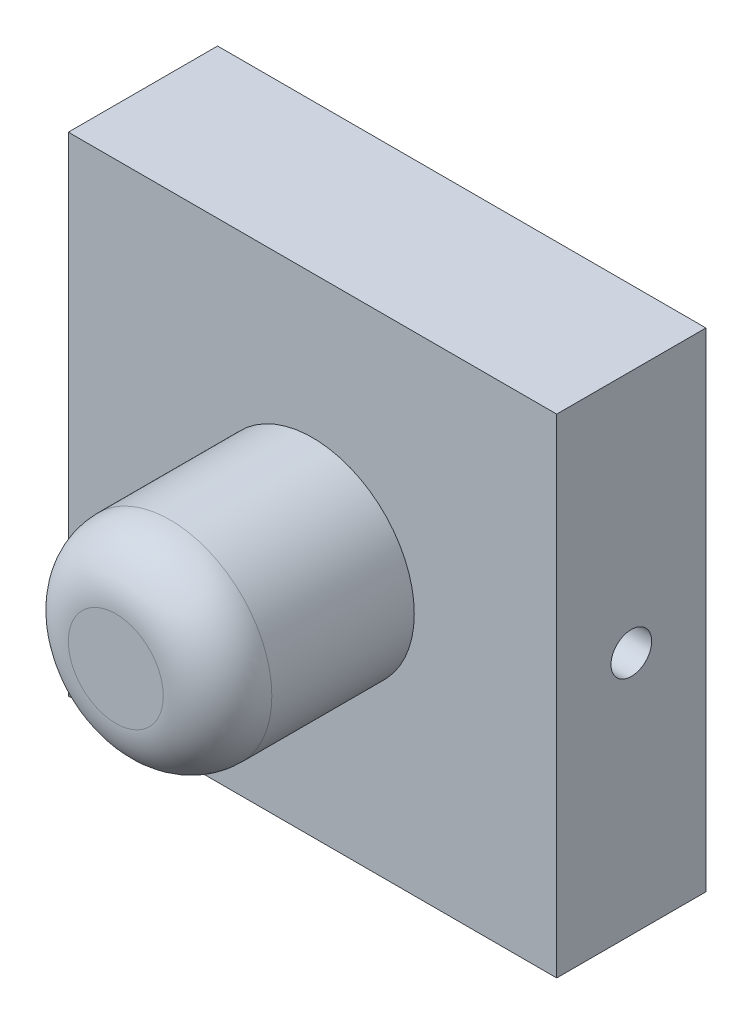
SolidWorks part; units mm, degrees
ref_plane "前视基准面" through (0, 0, 0) normal (0, 0, 1) x (1, 0, 0)
ref_plane "上视基准面" through (0, 0, 0) normal (0, 1, 0) x (1, 0, 0)
ref_plane "右视基准面" through (0, 0, 0) normal (1, 0, 0) x (0, 0, -1)
sketch "草图1" plane through (0, 0, 0) normal (1, 0, 0) x (0, 0, -1)
  line L1 (-5.5, -18) -> (5.5, -18)
  line L2 (-5.5, -18) -> (-5.5, 18)
  line L3 (-5.5, 18) -> (5.5, 18)
  line L4 (5.5, -18) -> (5.5, 18)
  line L5 (-5.5, -18) -> (5.5, 18) construction
  line L6 (-5.5, 18) -> (5.5, -18) construction
  point P0 (0, 0)
  dimension "D1" = 11
  dimension "D2" = 36
extrude "凸台-拉伸1" add sketch "草图1" along normal mid plane 36
sketch "草图2" plane through (0, 0, 0) normal (0, 0, 1) x (1, 0, 0)
  circle A0 centre (0, 0) radius 7.5
  dimension "D1" = 15
  dimension "D2" = 0
extrude "凸台-拉伸2" add sketch "草图2" along normal blind 20
fillet "圆角3" radius 4 1 edges at (7.5, 0, 20)
sketch "草图3" plane through (-18, 0, 0) normal (-1, 0, 0) x (0, 0, 1)
  circle A0 centre (0, 0) radius 1.5
  dimension "D1" = 3
extrude "切除-拉伸1" cut sketch "草图3" against normal through all
